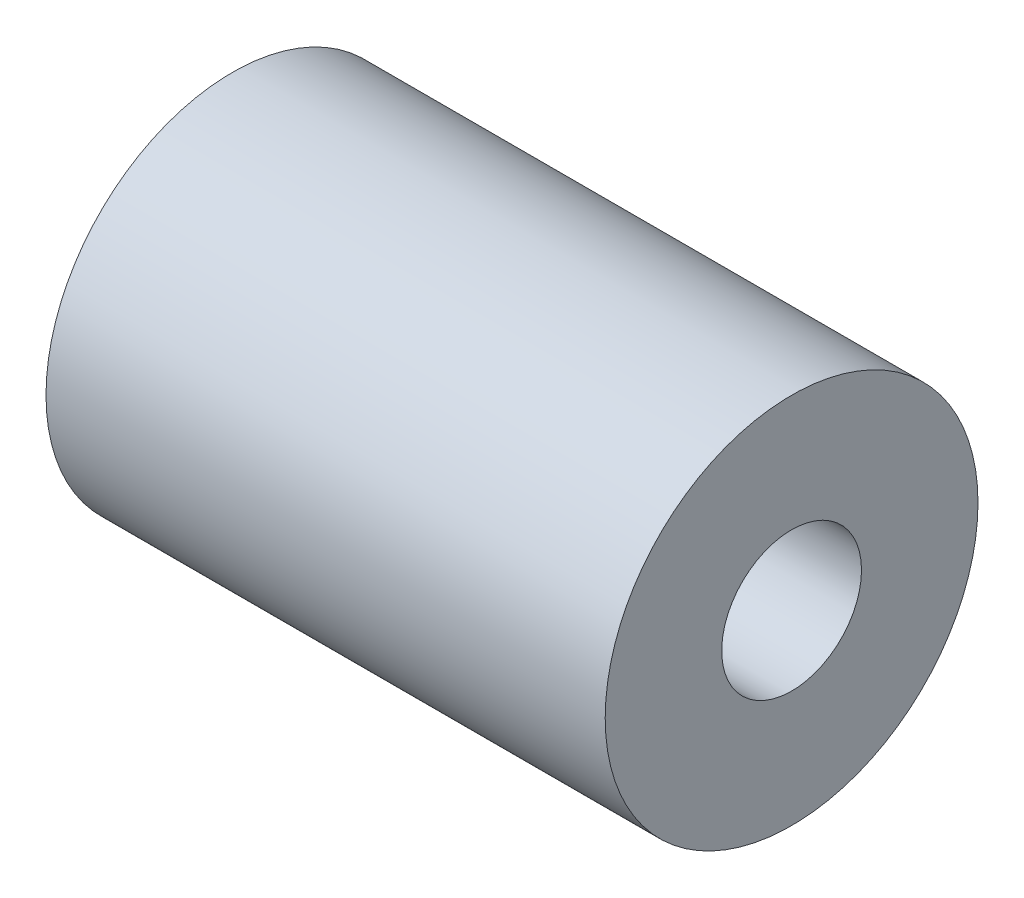
SolidWorks part; units mm, degrees
ref_plane "Alzado" through (0, 0, 0) normal (0, 0, 1) x (1, 0, 0)
ref_plane "Planta" through (0, 0, 0) normal (0, 1, 0) x (1, 0, 0)
ref_plane "Vista lateral" through (0, 0, 0) normal (1, 0, 0) x (0, 0, -1)
sketch "Croquis1" plane through (0, 0, 0) normal (1, 0, 0) x (0, 0, -1)
  circle A0 centre (0, 0) radius 1.5
  circle A1 centre (0, 0) radius 4
  dimension "D1" = 3
  dimension "D2" = 8
extrude "Saliente-Extruir1" add sketch "Croquis1" along normal blind 12
